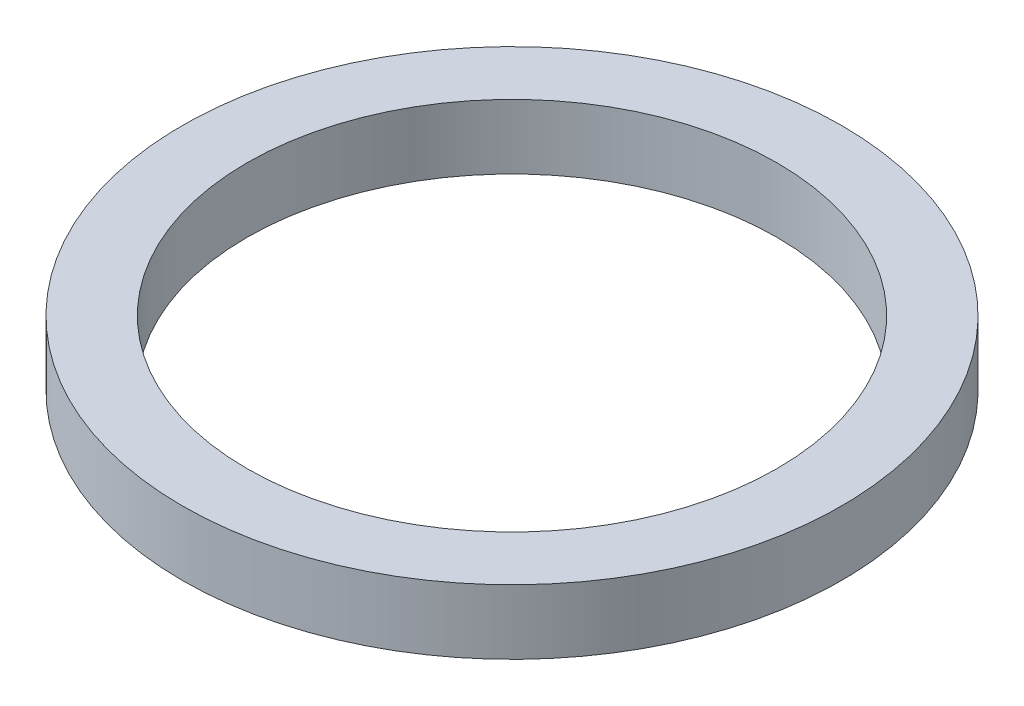
SolidWorks part; units mm, degrees
ref_plane "Front Plane" through (0, 0, 0) normal (0, 0, 1) x (1, 0, 0)
ref_plane "Top Plane" through (0, 0, 0) normal (0, 1, 0) x (1, 0, 0)
ref_plane "Right Plane" through (0, 0, 0) normal (1, 0, 0) x (0, 0, -1)
sketch "Sketch2" plane through (0, 0, 0) normal (0, 1, 0) x (1, 0, 0)
  circle A0 centre (0, 0) radius 12.75
  circle A1 centre (0, 0) radius 10.25
  dimension "D1" = 20.5
  dimension "D2" = 25.5
extrude "Boss-Extrude1" add sketch "Sketch2" along normal blind 2.5
